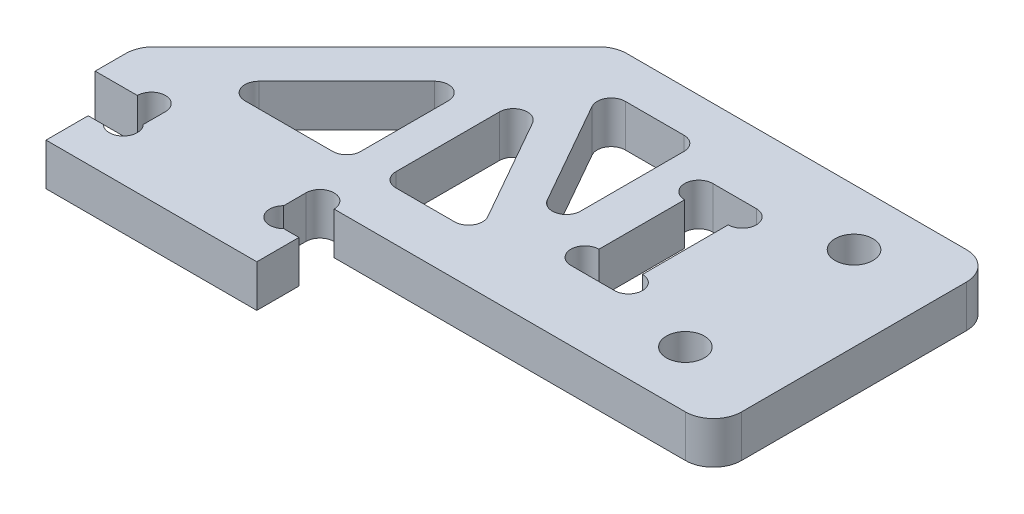
SolidWorks part; units mm, degrees
material "Thornel Mat VMA"
ref_plane "前视基准面" through (0, 0, 0) normal (0, 0, 1) x (1, 0, 0)
ref_plane "上视基准面" through (0, 0, 0) normal (0, 1, 0) x (1, 0, 0)
ref_plane "右视基准面" through (0, 0, 0) normal (1, 0, 0) x (0, 0, -1)
sketch "草图1" plane through (0, 0, 0) normal (0, 1, 0) x (1, 0, 0)
  line L0 (0, 0) -> (5, 0)
  line L3 (17, 20) -> (44, 20)
  line L5 (5, 0) -> (5, -3)
  line L6 (5, -3) -> (15, -3)
  line L7 (15, 0) -> (15, -3)
  line L8 (44, 20) -> (44, 0)
  line L9 (15, 0) -> (44, 0)
  line L10 (17, 20) -> (0, 3)
  line L11 (0, 3) -> (0, 0)
  line L12 (10, -3) -> (10, 13) construction
  dimension "D1" = 44
  dimension "D2" = 10
  dimension "D3" = 3
  dimension "D4" = 20
  dimension "D5" = 3
  dimension "D6" = 10
  dimension "D7" = 135
extrude "凸台-拉伸1" add sketch "草图1" along normal blind 3
sketch "草图2" plane through (0, 0, 0) normal (0, -1, 0) x (1, 0, 0)
  line L0 (32, -10) -> (44, -10) construction
  line L1 (32, -15.05) -> (28.9, -15.05)
  line L2 (32, -15.05) -> (32, -4.95)
  line L3 (32, -4.95) -> (28.9, -4.95)
  line L4 (28.9, -15.05) -> (28.9, -4.95)
  line L5 (44, 0) -> (44, -20) construction
  line L6 (38, -16) -> (38, -10) construction
  circle A0 centre (38, -16) radius 1.35
  circle A1 centre (38, -4) radius 1.35
  dimension "D4" = 2.7
  dimension "D1" = 12
  dimension "D2" = 3.1
  dimension "D3" = 10.1
  dimension "D5" = 12
extrude "切除-拉伸1" cut sketch "草图2" against normal through all
sketch "草图5" plane through (0, 3, 0) normal (0, 1, 0) x (1, 0, 0)
  line L0 (5, -3) -> (15, -3) construction
  line L1 (2.5, -6) -> (17.5, -6)
  line L2 (2.5, -6) -> (2.5, -3)
  line L3 (2.5, -3) -> (17.5, -3)
  line L4 (17.5, -6) -> (17.5, -3)
  line L5 (2.5, -6) -> (17.5, -3) construction
  line L6 (2.5, -3) -> (17.5, -6) construction
  line L7 (10, -3) -> (10, -4.5) construction
  point P0 (10, -4.5)
  dimension "D1" = 3
  dimension "D2" = 15
extrude "凸台-拉伸2" add sketch "草图5" against normal up to surface (3 mm away) up to face at (30.45, 0, -10)
sketch "草图3" plane through (0, 0, 0) normal (0, -1, 0) x (1, 0, 0)
  line L0 (32, -15.05) -> (32, -4.95) construction
  line L1 (28.9, -10) -> (30.45, -10) construction
  line L2 (28.9, -4.95) -> (28.9, -15.05) construction
  line L3 (30.45, -10) -> (30.45, -4.95) construction
  line L4 (32, -4.95) -> (28.9, -4.95) construction
  line L5 (15, 0) -> (44, 0) construction
  line L6 (10, 6) -> (10, 0) construction
  line L8 (2.5, 6) -> (17.5, 6) construction
  line L10 (4.2929, 2.2929) -> (5, 3) construction
  line L11 (5, 3) -> (2.5, 3) construction
  circle A0 centre (32, -14.05) radius 1
  circle A1 centre (16, 0) radius 1
  circle A2 centre (4, 0) radius 1
  circle A3 centre (32, -5.95) radius 1
  circle A4 centre (28.9, -5.95) radius 1
  circle A5 centre (28.9, -14.05) radius 1
  circle A6 centre (4.2929, 2.2929) radius 1
  circle A7 centre (15.7071, 2.2929) radius 1
  dimension "D1" = 2
  dimension "D2" = 45
extrude "切除-拉伸2" cut sketch "草图3" against normal through all
sketch "草图4" plane through (0, 3, 0) normal (0, 1, 0) x (1, 0, 0)
  line L0 (25.9, 17) -> (18.2426, 17)
  line L1 (18.2426, 17) -> (4.7426, 3.5)
  line L2 (4.7426, 3.5) -> (25.9, 3.5)
  line L3 (25.9, 3.5) -> (25.9, 17)
  line L4 (25.9, 3.5) -> (18.2426, 17) construction
  line L5 (19.0064, 17) -> (25.9, 4.8466)
  line L6 (23.7896, 3.5) -> (16.8961, 15.6534)
  line L7 (17, 20) -> (0, 3) construction
  line L8 (17, 0) -> (44, 0) construction
  line L9 (28.9, 6.95) -> (28.9, 13.05) construction
  line L10 (44, 20) -> (17, 20) construction
  line L11 (16.8961, 15.6534) -> (16.8961, 3.5)
  line L12 (14.3961, 13.1534) -> (14.3961, 3.5)
  dimension "D1" = 3
  dimension "D2" = 3.5
  dimension "D3" = 3
  dimension "D4" = 3
  dimension "D5" = 2.5
  dimension "D6" = 2.5
extrude "切除-拉伸3" cut sketch "草图4" against normal blind 10 contours L6 L11 L2 | L12 L1 L2 | L0 L5 L3
fillet "圆角1" radius 1 9 edges at (14.3961, 1.5, -3.5) (4.7426, 1.5, -3.5) (14.3961, 1.5, -13.1534) (16.8961, 1.5, -3.5) (23.7896, 1.5, -3.5) (16.8961, 1.5, -15.6534) (25.9, 1.5, -4.8466) (25.9, 1.5, -17) (19.0064, 1.5, -17)
fillet "圆角2" radius 2 4 edges at (44, 1.5, 0) (44, 1.5, -20) (0, 1.5, -3) (17, 1.5, -20)
